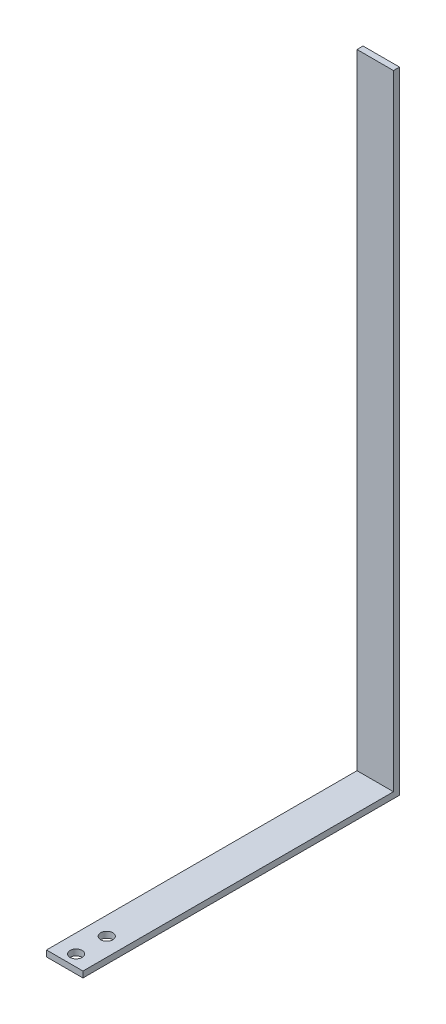
SolidWorks part; units mm, degrees
ref_plane "Alzado" through (0, 0, 0) normal (0, 0, 1) x (1, 0, 0)
ref_plane "Planta" through (0, 0, 0) normal (0, 1, 0) x (1, 0, 0)
ref_plane "Vista lateral" through (0, 0, 0) normal (1, 0, 0) x (0, 0, -1)
sketch "Croquis1" plane through (0, 0, 0) normal (0, 0, 1) x (1, 0, 0)
  line L1 (-19.05, 3.155) -> (19.05, 3.155)
  line L2 (-19.05, 3.155) -> (-19.05, -3.155)
  line L3 (-19.05, -3.155) -> (19.05, -3.155)
  line L4 (19.05, 3.155) -> (19.05, -3.155)
  line L5 (-19.05, 3.155) -> (19.05, -3.155) construction
  line L6 (-19.05, -3.155) -> (19.05, 3.155) construction
  point P0 (0, 0)
  dimension "D1" = 38.1
  dimension "D2" = 6.31
extrude "Saliente-Extruir1" add sketch "Croquis1" along normal blind 330.7
sketch "Croquis3" plane through (0, -3.155, 0) normal (0, -1, 0) x (1, 0, 0)
  line L0 (-19.05, 330.7) -> (-19.05, 0) construction
  line L1 (19.05, 0) -> (-19.05, 0)
  line L2 (19.05, 0) -> (19.05, 6.31)
  line L3 (19.05, 6.31) -> (-19.05, 6.31)
  line L4 (-19.05, 0) -> (-19.05, 6.31)
  line L5 (19.05, 0) -> (-19.05, 6.31) construction
  line L6 (19.05, 6.31) -> (-19.05, 0) construction
  line L7 (19.05, 330.7) -> (19.05, 0) construction
  line L8 (-19.05, 0) -> (19.05, 0) construction
  point P0 (0, 3.155)
  dimension "D1" = 6.31
extrude "Saliente-Extruir2" add sketch "Croquis3" against normal blind 658.79
sketch "Croquis4" plane through (0, -3.155, 0) normal (0, -1, 0) x (-1, 0, 0)
  circle A0 centre (0, -286.8078) radius 6.35
  circle A1 centre (0, -318.8078) radius 6.35
extrude "Cortar-Extruir1" cut sketch "Croquis4" against normal blind 6.31
